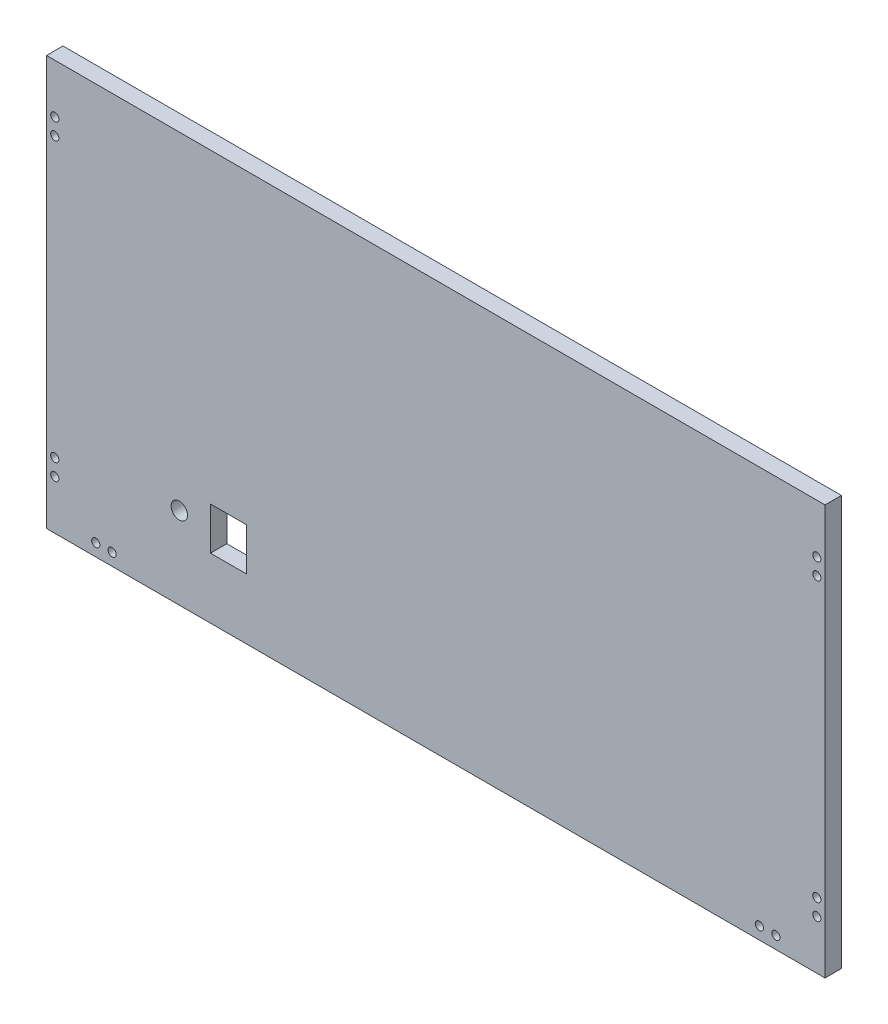
SolidWorks part; units mm, degrees
ref_plane "Front Plane" through (0, 0, 0) normal (0, 0, 1) x (1, 0, 0)
ref_plane "Top Plane" through (0, 0, 0) normal (0, 1, 0) x (1, 0, 0)
ref_plane "Right Plane" through (0, 0, 0) normal (1, 0, 0) x (0, 0, -1)
sketch "Sketch1" plane through (0, 0, 0) normal (0, 0, 1) x (1, 0, 0)
  line L1 (-237.5, 125) -> (237.5, 125)
  line L2 (-237.5, 125) -> (-237.5, -125)
  line L3 (-237.5, -125) -> (237.5, -125)
  line L4 (237.5, 125) -> (237.5, -125)
  line L5 (-237.5, 125) -> (237.5, -125) construction
  line L6 (-237.5, -125) -> (237.5, 125) construction
  point P0 (0, 0)
  dimension "D1" = 250
  dimension "D2" = 475
extrude "Boss-Extrude1" add sketch "Sketch1" along normal blind 10
sketch "Sketch2" plane through (0, 0, 10) normal (0, 0, 1) x (1, 0, 0)
  line L0 (-237.5, -125) -> (237.5, -125) construction
  line L1 (-237.5, 125) -> (-237.5, -125) construction
  line L2 (237.5, -125) -> (237.5, 125) construction
  line L3 (-237.5, -125) -> (237.5, -125) construction
  circle A0 centre (-207.5, -117.5) radius 2.5
  circle A3 centre (207.5, -117.5) radius 2.5
  circle A4 centre (197.5, -117.5) radius 2.5
  circle A5 centre (-197.5, -117.5) radius 2.5
  dimension "D2" = 5
  dimension "D6" = 5
  dimension "D1" = 7.5
  dimension "D3" = 30
  dimension "D5" = 30
  dimension "D7" = 7.5
  dimension "D8" = 10
  dimension "D4" = 2
extrude "Cut-Extrude1" cut sketch "Sketch2" against normal through all
sketch "Sketch3" plane through (0, 0, 0) normal (0, 0, -1) x (-1, 0, 0)
  line L0 (237.5, 125) -> (237.5, -125) construction
  line L1 (237.5, -125) -> (-237.5, -125) construction
  line L2 (-237.5, 125) -> (237.5, 125) construction
  line L3 (-237.5, -125) -> (-237.5, 125) construction
  circle A0 centre (232.5, 95) radius 2.5
  circle A1 centre (232.5, 85) radius 2.5
  circle A2 centre (232.5, -85) radius 2.5
  circle A3 centre (232.5, -95) radius 2.5
  circle A4 centre (-232.5, 95) radius 2.5
  circle A5 centre (-232.5, 85) radius 2.5
  circle A6 centre (-232.5, -85) radius 2.5
  circle A7 centre (-232.5, -95) radius 2.5
  dimension "D1" = 5
  dimension "D2" = 5
  dimension "D3" = 30
  dimension "D4" = 10
  dimension "D5" = 30
  dimension "D6" = 10
  dimension "D7" = 5
extrude "Cut-Extrude2" cut sketch "Sketch3" against normal through all
sketch "Sketch4" plane through (0, 0, 0) normal (0, 0, -1) x (-1, 0, 0)
  line L0 (237.5, 125) -> (237.5, -125) construction
  line L1 (115.5, -62) -> (137.5, -62)
  line L2 (115.5, -62) -> (115.5, -88)
  line L3 (115.5, -88) -> (137.5, -88)
  line L4 (137.5, -62) -> (137.5, -88)
  line L5 (115.5, -62) -> (137.5, -88) construction
  line L6 (115.5, -88) -> (137.5, -62) construction
  line L7 (237.5, -125) -> (-237.5, -125) construction
  circle A0 centre (156.5, -75) radius 5
  point P2 (126.5, -75)
  point P7 (137.5, -75)
  point P12 (0, 0)
  point P13 (162.7707, -2.5241)
  point P14 (0, 0)
  dimension "D6" = 10
  dimension "D1" = 100
  dimension "D2" = 50
  dimension "D3" = 22
  dimension "D4" = 26
  dimension "D5" = 30
extrude "Cut-Extrude3" cut sketch "Sketch4" against normal through all
